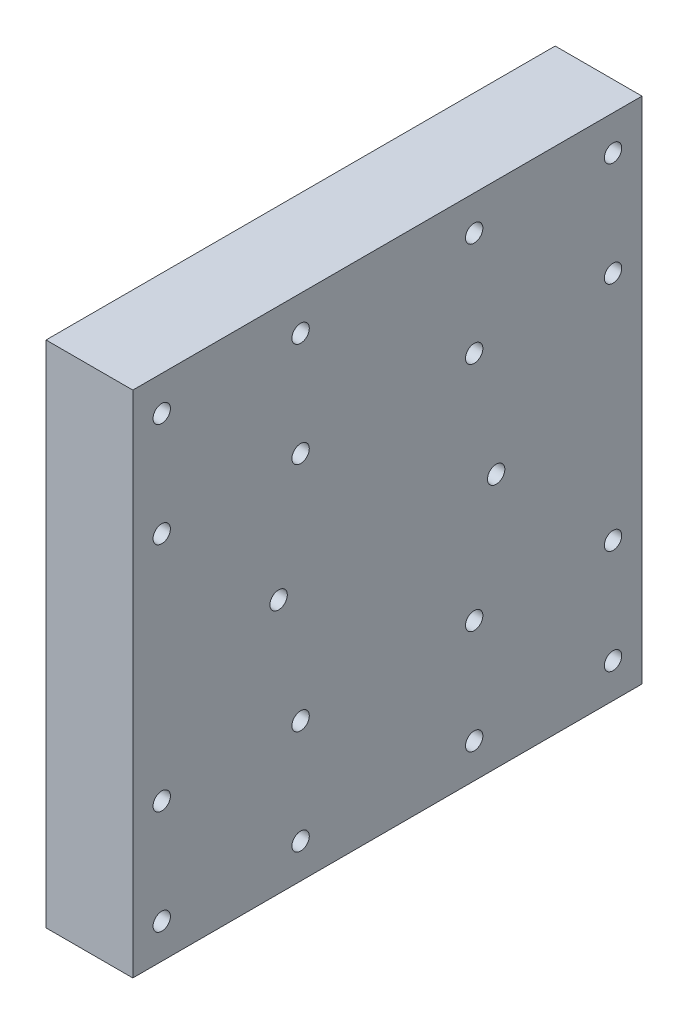
SolidWorks part; units mm, degrees
ref_plane "Alzado" through (0, 0, 0) normal (0, 0, 1) x (1, 0, 0)
ref_plane "Planta" through (0, 0, 0) normal (0, 1, 0) x (1, 0, 0)
ref_plane "Vista lateral" through (0, 0, 0) normal (1, 0, 0) x (0, 0, -1)
sketch "Croquis1" plane through (0, 0, 0) normal (1, 0, 0) x (0, 0, -1)
  line L0 (44, 88) -> (44, 0) construction
  line L1 (0, 0) -> (88, 0)
  line L2 (0, 0) -> (0, 88)
  line L3 (0, 88) -> (88, 88)
  line L4 (88, 0) -> (88, 88)
  line L5 (0, 44) -> (88, 44) construction
  circle A0 centre (5, 82) radius 1.5
  circle A1 centre (29, 82) radius 1.5
  circle A2 centre (29, 64) radius 1.5
  circle A3 centre (5, 64) radius 1.5
  circle A4 centre (59, 64) radius 1.5
  circle A5 centre (59, 82) radius 1.5
  circle A6 centre (83, 64) radius 1.5
  circle A7 centre (83, 82) radius 1.5
  circle A8 centre (83, 24) radius 1.5
  circle A9 centre (59, 24) radius 1.5
  circle A10 centre (83, 6) radius 1.5
  circle A11 centre (59, 6) radius 1.5
  circle A12 centre (29, 24) radius 1.5
  circle A13 centre (5, 24) radius 1.5
  circle A14 centre (29, 6) radius 1.5
  circle A15 centre (5, 6) radius 1.5
  circle A16 centre (25.2, 44) radius 1.5
  circle A17 centre (62.8, 44) radius 1.5
  dimension "D3" = 3
  dimension "D8" = 3
  dimension "D1" = 88
  dimension "D2" = 88
  dimension "D4" = 5
  dimension "D5" = 6
  dimension "D6" = 24
  dimension "D7" = 18
  dimension "D9" = 37.6
  dimension "D10" = 18.8
extrude "Saliente-Extruir1" add sketch "Croquis1" along normal blind 15
